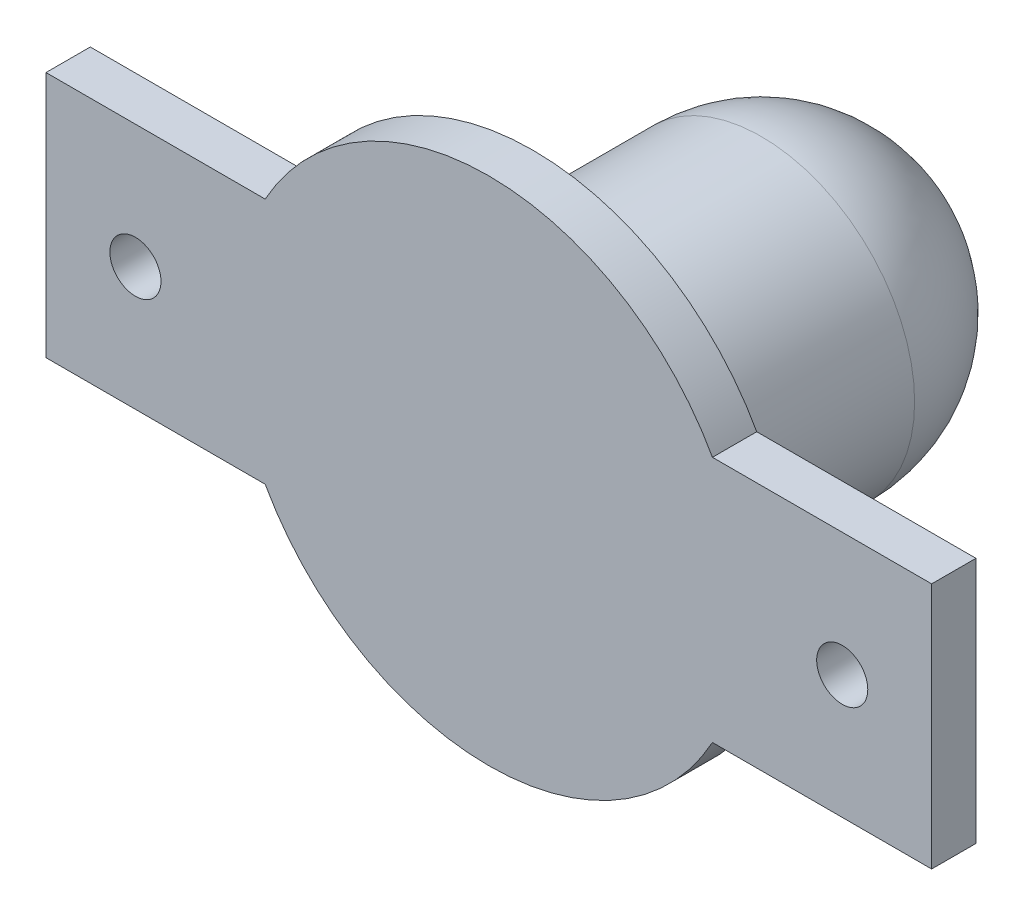
SolidWorks part; units mm, degrees
ref_plane "Front Plane" through (0, 0, 0) normal (0, 0, 1) x (1, 0, 0)
ref_plane "Top Plane" through (0, 0, 0) normal (0, 1, 0) x (1, 0, 0)
ref_plane "Right Plane" through (0, 0, 0) normal (1, 0, 0) x (0, 0, -1)
sketch "Sketch1" plane through (0, 0, 0) normal (0, 0, 1) x (1, 0, 0)
  line L0 (-22.8947, 0) -> (28.2632, 0) construction
  line L1 (-26, -7.25) -> (-26, 7.25)
  line L2 (-26, 7.25) -> (-13.13, 7.25)
  line L3 (0, 25.0658) -> (0, -23.0132) construction
  line L4 (26, 7.25) -> (13.13, 7.25)
  line L5 (26, -7.25) -> (26, 7.25)
  line L6 (26, -7.25) -> (13.13, -7.25)
  line L7 (-26, -7.25) -> (-13.13, -7.25)
  arc A1 (-13.13, 7.25) -> (13.13, 7.25) centre (0, 0) cw
  arc A2 (-13.13, -7.25) -> (13.13, -7.25) centre (0, 0) ccw
  point P5 (26, 0)
  point P17 (-26, 0)
  dimension "D2" = 26
  dimension "D3" = 7.25
  dimension "D4" = 12.87
extrude "Boss-Extrude2" add sketch "Sketch1" against normal blind 2.6
sketch "Sketch2" plane through (0, 0, 0) normal (0, 0, 1) x (1, 0, 0)
  circle A0 centre (0, 0) radius 9
  dimension "D1" = 18
extrude "Boss-Extrude3" add sketch "Sketch2" against normal blind 16
sketch "Sketch3" plane through (0, 0, -16) normal (0, 0, -1) x (-1, 0, 0)
  line L0 (-9, 0) -> (9, 0) construction
  line L1 (-9, 0) -> (9, 0)
  arc A0 (-9, 0) -> (9, 0) centre (0, 0) cw
  circle A1 centre (0, 0) radius 9 construction
  circle A2 centre (0, 0) radius 9 construction
revolve "Revolve1" add sketch "Sketch3" angle 180 about L0
sketch "Sketch4" plane through (0, 0, 0) normal (0, 0, 1) x (1, 0, 0)
  circle A0 centre (0, 0) radius 9
  dimension "D1" = 18
sketch "Sketch5" plane through (0, 0, 0) normal (0, 0, 1) x (1, 0, 0)
  circle A0 centre (-20.75, 0) radius 1.5
  circle A1 centre (20.75, 0) radius 1.5
  dimension "D1" = 3
  dimension "D2" = 3
  dimension "D3" = 41.5
  dimension "D4" = 20.75
extrude "Cut-Extrude1" cut sketch "Sketch5" against normal blind 16
